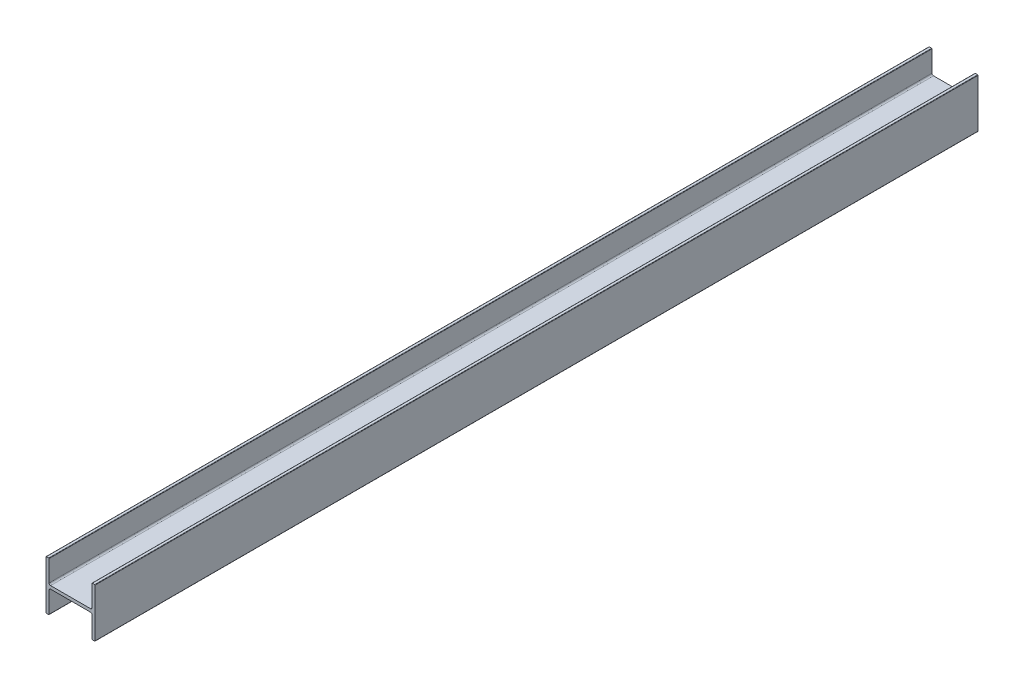
SolidWorks part; units mm, degrees
ref_plane "Front" through (0, 0, 0) normal (0, 0, 1) x (1, 0, 0)
ref_plane "Top" through (0, 0, 0) normal (0, 1, 0) x (1, 0, 0)
ref_plane "Right" through (0, 0, 0) normal (1, 0, 0) x (0, 0, -1)
sketch "Sketch1" plane through (0, 0, 0) normal (0, 0, 1) x (1, 0, 0)
  line L0 (25.4, -25.4) -> (25.4, 25.4) construction
  line L1 (-25.4, 25.4) -> (-25.4, -25.4) construction
  line L2 (25.4, 0) -> (-25.4, 0) construction
  line L3 (-25.4, -25.4) -> (-22.225, -25.4) construction
  line L4 (25.4, -25.4) -> (22.225, -25.4) construction
  dimension "Outside Height" = 50.8
  dimension "Wall Thickness" = 3.175
  dimension "Inside Width" = 44.45
  dimension "Outside Width" = 50.8
sketch "Sketch2" plane through (0, 0, 0) normal (1, 0, 0) x (0, 0, -1)
  line L0 (-457.2, 25.4) -> (457.2, 25.4) construction
  point P2 (-406.4, 25.4)
  point P4 (406.4, 25.4)
  dimension "Length" = 914.4
  dimension "D1" = 50.8
  dimension "D2" = 50.8
sketch "Sketch3" plane through (0, 0, 0) normal (0, 0, 1) x (1, 0, 0)
  line L0 (25.4, -25.4) -> (25.4, 25.4)
  line L1 (25.4, 25.4) -> (22.225, 25.4)
  line L2 (22.225, 25.4) -> (22.225, 1.5875)
  line L3 (22.225, 1.5875) -> (-22.225, 1.5875)
  line L4 (-22.225, 1.5875) -> (-22.225, 25.4)
  line L5 (-22.225, 25.4) -> (-25.4, 25.4)
  line L6 (-25.4, 25.4) -> (-25.4, -25.4)
  line L7 (-25.4, -25.4) -> (-22.225, -25.4)
  line L8 (-22.225, -25.4) -> (-22.225, -1.5875)
  line L9 (-22.225, -1.5875) -> (22.225, -1.5875)
  line L10 (22.225, -1.5875) -> (22.225, -25.4)
  line L11 (22.225, -25.4) -> (25.4, -25.4)
  line L12 (25.4, -25.4) -> (25.4, 25.4) construction
  line L13 (0, 1.5875) -> (0, -1.5875) construction
extrude "Boss-Extrude1" add sketch "Sketch3" along normal up to vertex (457.2 mm away) and the other way up to vertex (457.2 mm away) up to point (0, 25.4, 457.2) other way up to point (0, 25.4, -457.2)
fillet "Fillet1" radius 1.5875 4 edges at (-22.225, -1.5875, 0) (22.225, -1.5875, 0) (22.225, 1.5875, 0) (-22.225, 1.5875, 0)
fillet "Fillet2" radius 0.3969 8 edges at (25.4, -25.4, 0) (22.225, -25.4, 0) (-22.225, -25.4, 0) (-25.4, -25.4, 0) (25.4, 25.4, 0) (22.225, 25.4, 0) (-22.225, 25.4, 0) (-25.4, 25.4, 0)
equation "\"D1@Sketch2\" = \"Outside Height@Sketch1\""
equation "\"D2@Sketch2\" = \"D1@Sketch2\""
equation "\"D1@Fillet1\"=\"Wall Thickness@Sketch1\" / 2"
equation "\"D1@Fillet2\"=\"Wall Thickness@Sketch1\" / 8"
